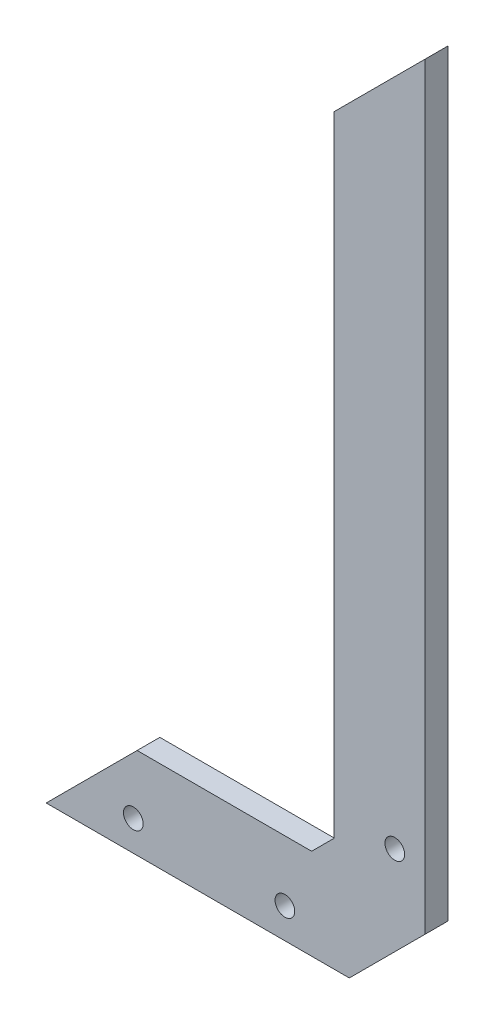
SolidWorks part; units mm, degrees
ref_plane "Front Plane" through (0, 0, 0) normal (0, 0, 1) x (1, 0, 0)
ref_plane "Top Plane" through (0, 0, 0) normal (0, 1, 0) x (1, 0, 0)
ref_plane "Right Plane" through (0, 0, 0) normal (1, 0, 0) x (0, 0, -1)
sketch "Sketch1" plane through (0, 0, 0) normal (0, 0, 1) x (1, 0, 0)
  line L0 (4.5, 10.2435) -> (44.5, 10.2435)
  line L1 (-15.5, 10.2435) -> (54.5, 10.2435) construction
  line L4 (54.5, 20.2435) -> (54.5, 120.2435)
  line L5 (54.5, 34.0079) -> (54.5, 130.2435) construction
  line L6 (54.5, 120.2435) -> (42.5, 108.2435)
  line L7 (42.5, 108.2435) -> (42.5, 25.2141)
  line L8 (42.5, 25.2141) -> (39.5294, 22.2435)
  line L9 (39.5294, 22.2435) -> (16.5, 22.2435)
  line L10 (16.5, 22.2435) -> (4.5, 10.2435)
  line L11 (44.5, 10.2435) -> (54.5, 20.2435)
  circle A4 centre (16, 14.2435) radius 1.3
  circle A5 centre (36, 14.2435) radius 1.3
  circle A6 centre (-4, 14.2435) radius 1.3 construction
  circle A7 centre (50.5, 28.0035) radius 1.3
  dimension "D8" = 4
  dimension "D9" = 4
  dimension "D10" = 20
  dimension "D11" = 20
  dimension "D1" = 12
  dimension "D2" = 12
  dimension "D3" = 45
  dimension "D4" = 12
  dimension "D5" = 10
  dimension "D6" = 40
  dimension "D7" = 100
extrude "Extrude1" add sketch "Sketch1" along normal blind 3
